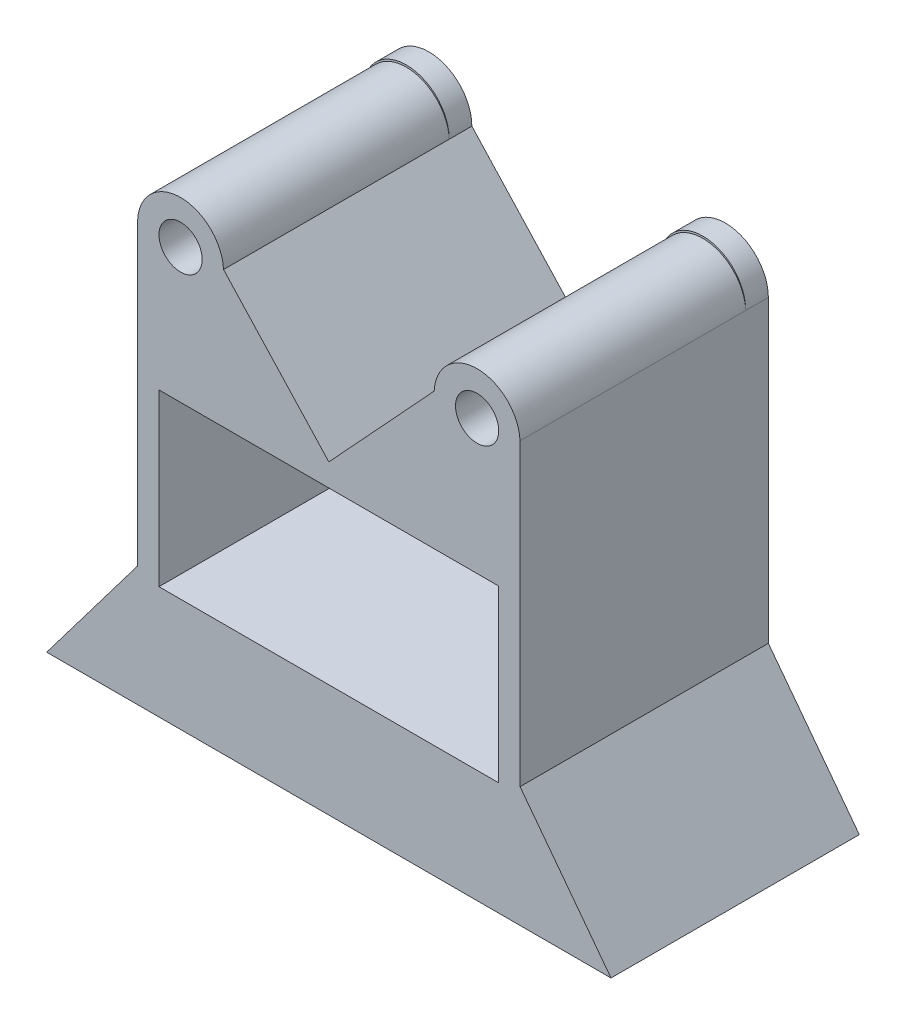
SolidWorks part; units mm, degrees
ref_plane "Front Plane" through (0, 0, 0) normal (0, 0, 1) x (1, 0, 0)
ref_plane "Top Plane" through (0, 0, 0) normal (0, 1, 0) x (1, 0, 0)
ref_plane "Right Plane" through (0, 0, 0) normal (1, 0, 0) x (0, 0, -1)
sketch "Sketch1" plane through (0, 0, 0) normal (0, 0, 1) x (1, 0, 0)
  line L0 (0, 0) -> (0, 54.0315) construction
  line L1 (-38.227, -19.177) -> (38.227, -19.177)
  line L2 (-38.227, -19.177) -> (-38.227, 19.177)
  line L3 (-38.227, 19.177) -> (38.227, 19.177)
  line L4 (38.227, -19.177) -> (38.227, 19.177)
  line L5 (-38.227, -19.177) -> (38.227, 19.177) construction
  line L6 (-38.227, 19.177) -> (38.227, -19.177) construction
  line L7 (0, 54.0315) -> (0, -50.3288) construction
  line L8 (-38.227, 7.4711) -> (-38.227, 58.2157) construction
  line L9 (-43.03, -17.5223) -> (-43.03, 19.177)
  line L10 (-63.5, -44.577) -> (63.5, -44.577)
  line L11 (-43.03, -17.5223) -> (-63.5, -44.577)
  line L12 (-43.03, -17.5223) -> (-43.03, 56.2622) construction
  line L13 (-43.03, 19.177) -> (-43.03, 49.8911)
  line L14 (-23.6995, 49.9018) -> (0, 24.257)
  line L15 (43.03, -17.5223) -> (63.5, -44.577)
  line L16 (43.03, 19.177) -> (43.03, 49.8911)
  line L17 (43.03, -17.5223) -> (43.03, 19.177)
  line L18 (23.6995, 49.9018) -> (0, 24.257)
  circle A0 centre (-33.3645, 49.4395) radius 4.8625
  circle A1 centre (33.3645, 49.4395) radius 4.8625
  arc A2 (-43.03, 49.8911) -> (-23.6995, 49.9018) centre (-33.3645, 49.4395) cw
  arc A3 (43.03, 49.8911) -> (23.6995, 49.9018) centre (33.3645, 49.4395) ccw
  point P0 (0, 0)
  point P11 (-33.3645, 44.577)
  point P14 (-38.227, 49.4395)
  point P24 (0, 24.257)
  dimension "D3" = 9.725
  dimension "D1" = 76.454
  dimension "D2" = 38.354
  dimension "D4" = 0
  dimension "D5" = 25.4
  dimension "D6" = 5.08
  dimension "D7" = 63.5
  dimension "D9" = 25.4
  dimension "D10" = 5.08
extrude "Boss-Extrude1" add sketch "Sketch1" along normal blind 50.8
sketch "Sketch2" plane through (0, 0, 0) normal (0, 0, -1) x (-1, 0, 0)
  line L0 (-43.03, 49.8911) -> (-43.03, -17.5223)
  line L1 (-43.03, -17.5223) -> (-63.5, -44.577)
  line L2 (-63.5, -44.577) -> (63.5, -44.577)
  line L3 (63.5, -44.577) -> (43.03, -17.5223)
  line L4 (43.03, -17.5223) -> (43.03, 49.8911)
  line L5 (23.6995, 49.9018) -> (0, 24.257)
  line L6 (0, 24.257) -> (-23.6995, 49.9018)
  arc A0 (-43.03, 49.8911) -> (-23.6995, 49.9018) centre (-33.3648, 49.8911) cw
  arc A1 (23.6995, 49.9018) -> (43.03, 49.8911) centre (33.3648, 49.8911) cw
extrude "Boss-Extrude2" add sketch "Sketch2" along normal blind 5.08
